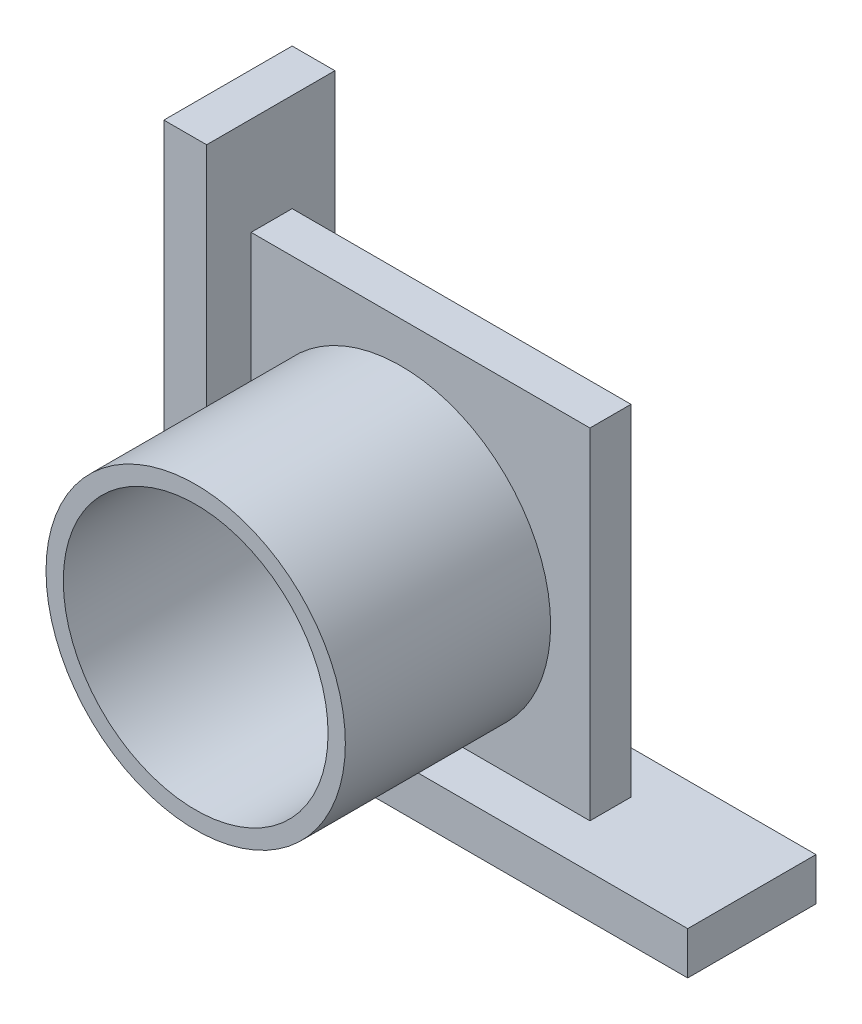
SolidWorks part; units mm, degrees
ref_plane "Front Plane" through (0, 0, 0) normal (0, 0, 1) x (1, 0, 0)
ref_plane "Top Plane" through (0, 0, 0) normal (0, 1, 0) x (1, 0, 0)
ref_plane "Right Plane" through (0, 0, 0) normal (1, 0, 0) x (0, 0, -1)
sketch "Sketch1" plane through (0, 0, 0) normal (-1, 0, 0) x (0, -1, 0)
  line L0 (0, -76.659) -> (0, 176.2699) construction
  line L1 (-45.4446, 0) -> (105.5783, 0) construction
  line L3 (0, 0) -> (-12.7, 0)
  line L4 (0, 0) -> (0, 38.1)
  line L5 (0, 38.1) -> (-12.7, 38.1)
  line L6 (-12.7, 0) -> (-12.7, 38.1)
  dimension "D1" = 38.1
  dimension "D2" = 12.7
extrude "Boss-Extrude1" add sketch "Sketch1" against normal blind 155.575
sketch "Sketch3" plane through (0, 12.7, 0) normal (0, 1, 0) x (1, 0, 0)
  line L0 (155.575, -38.1) -> (0, -38.1) construction
  line L1 (0, 0) -> (12.7, 0)
  line L2 (0, 0) -> (0, -38.1)
  line L3 (0, -38.1) -> (12.7, -38.1)
  line L4 (12.7, 0) -> (12.7, -38.1)
  dimension "D1" = 12.7
extrude "Boss-Extrude2" add sketch "Sketch3" along normal blind 130.175
sketch "Sketch4" plane through (0, 12.7, 0) normal (0, 1, 0) x (1, 0, 0)
  line L0 (12.7, -38.1) -> (12.7, 0) construction
  line L1 (12.7, -12.7) -> (113.3348, -12.7)
  line L2 (12.7, -12.7) -> (12.7, -24.892)
  line L3 (12.7, -24.892) -> (113.3348, -24.892)
  line L4 (113.3348, -12.7) -> (113.3348, -24.892)
  dimension "D1" = 100.6348
  dimension "D2" = 12.192
  dimension "D3" = 12.7
extrude "Boss-Extrude3" add sketch "Sketch4" along normal blind 101.0412
sketch "Sketch5" plane through (0, 0, 24.892) normal (0, 0, 1) x (1, 0, 0)
  line L0 (12.7, 58.42) -> (58.42, 12.7)
  line L1 (12.7, 113.7412) -> (12.7, 12.7) construction
  line L2 (155.575, 12.7) -> (12.7, 12.7) construction
  line L3 (58.42, 12.7) -> (12.7, 12.7)
  line L4 (12.7, 12.7) -> (12.7, 58.42)
  dimension "D1" = 45.72
  dimension "D2" = 45.72
sketch "Sketch7" plane through (0, 0, 0) normal (0, 1, 0) x (1, 0, 0)
  line L0 (0, 66.6649) -> (0, -63.5607) construction
  line L1 (-10.7252, -85.852) -> (133.7438, -85.852) construction
  line L3 (12.7, -24.892) -> (113.3348, -24.892) construction
  dimension "D1" = 60.96
sketch "Sketch6" plane through (0, 0, 24.892) normal (0, 0, -1) x (-1, 0, 0)
  line L3 (-57.2008, 61.6364) -> (-57.2008, 4.9884) construction
  line L4 (-61.9953, 57.2008) -> (-4.3021, 57.2008) construction
  line L5 (-113.3348, 12.7) -> (-12.7, 12.7) construction
  line L6 (-12.7, 12.7) -> (-12.7, 58.42) construction
  circle A0 centre (-57.2008, 57.2008) radius 44.45
  circle A1 centre (-57.2008, 57.2008) radius 39.3192
  point P8 (-12.7508, 57.2008)
  point P9 (-57.2008, 12.7508)
  dimension "D1" = 88.9
  dimension "D3" = 0.0508
  dimension "D4" = 0.0508
  dimension "D2" = 5.1308
ref_plane "Plane1" through (0, 0, 85.852) normal (0, 0, 1) x (1, 0, 0)
extrude "Cut-Extrude2" cut sketch "Sketch5" against normal up to surface (12.192 mm away) up to face at (63.0174, 63.2206, 12.7)
extrude "Boss-Extrude8" add sketch "Sketch6" along normal up to surface (60.96 mm away) from surface at -60.96 contours A1
